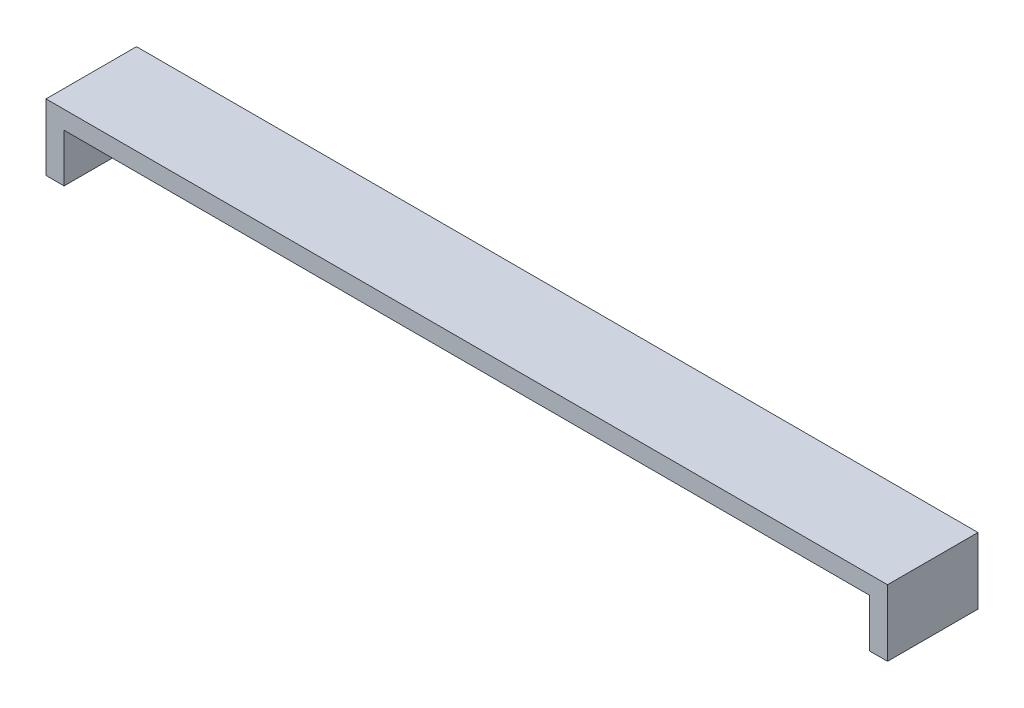
SolidWorks part; units mm, degrees
ref_plane "Front Plane" through (0, 0, 0) normal (0, 0, 1) x (1, 0, 0)
ref_plane "Top Plane" through (0, 0, 0) normal (0, 1, 0) x (1, 0, 0)
ref_plane "Right Plane" through (0, 0, 0) normal (1, 0, 0) x (0, 0, -1)
sketch "Sketch1" plane through (0, 0, 0) normal (0, 0, 1) x (1, 0, 0)
  line L0 (-66.75, -4) -> (-69.75, -4)
  line L1 (-66.75, 4) -> (66.75, 4)
  line L2 (-66.75, 4) -> (-66.75, -4)
  line L4 (66.75, 4) -> (66.75, -4)
  line L7 (-69.75, -4) -> (-69.75, 7)
  line L8 (-69.75, 7) -> (69.75, 7)
  line L9 (69.75, 7) -> (69.75, -4)
  line L10 (69.75, -4) -> (66.75, -4)
  point P0 (0, 0)
extrude "Boss-Extrude1" add sketch "Sketch1" along normal blind 15
